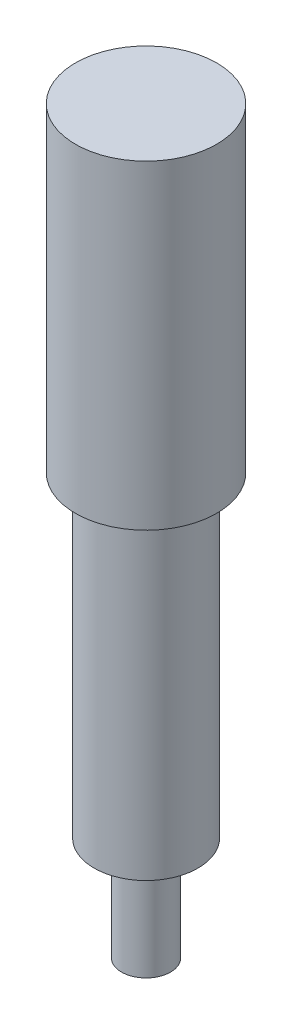
SolidWorks part; units mm, degrees
material "AISI 316 Annealed Stainless Steel Bar (SS)"
ref_plane "Front Plane" through (0, 0, 0) normal (0, 0, 1) x (1, 0, 0)
ref_plane "Top Plane" through (0, 0, 0) normal (0, 1, 0) x (1, 0, 0)
ref_plane "Right Plane" through (0, 0, 0) normal (1, 0, 0) x (0, 0, -1)
sketch "Sketch2" plane through (0, 0, 0) normal (0, 0, 1) x (1, 0, 0)
  line L0 (0, 0) -> (0, 508.8276) construction
  line L1 (0, 0) -> (6, 0)
  line L2 (0, 0) -> (0, 25.4)
  line L3 (0, 25.4) -> (6, 25.4)
  line L4 (6, 0) -> (6, 25.4)
  line L5 (0, 25.4) -> (12.721, 25.4)
  line L6 (0, 25.4) -> (0, 69.85)
  line L7 (0, 69.85) -> (12.721, 69.85)
  line L8 (12.721, 25.4) -> (12.721, 69.85)
  line L9 (0, 69.85) -> (12.721, 69.85)
  line L10 (0, 69.85) -> (0, 102.87)
  line L11 (0, 102.87) -> (12.721, 102.87)
  line L12 (12.721, 69.85) -> (12.721, 102.87)
  line L13 (0, 102.87) -> (17.272, 102.87)
  line L14 (0, 102.87) -> (0, 181.102)
  line L15 (0, 181.102) -> (17.272, 181.102)
  line L16 (17.272, 102.87) -> (17.272, 181.102)
  dimension "D1" = 78.232
  dimension "D2" = 17.272
  dimension "D4" = 33.02
  dimension "D3" = 12.721
  dimension "D5" = 44.45
  dimension "D6" = 12.721
  dimension "D7" = 25.4
  dimension "D8" = 6
revolve "Revolve1" add sketch "Sketch2" angle 360 about L0
equation "\"hole diamiter\"= 1.36in"
equation "\"wheel depth\"= 2.88"
equation "\"press_tolerance\"= 0.00165"
equation "\"wheel_connection\"= \"hole diamiter\"'https://at-machining.com/tolerance-press-fit/"
equation "\"D1@Sketch2\"=\"wheel depth\"+0.2"
equation "\"D2@Sketch2\"=\"wheel_connection\"/2"
equation "\"fitting depth\"= 1.3"
equation "\"D4@Sketch2\"=\"fitting depth\""
equation "\"bearing_id\"= 1"
equation "\"bearing_connection\"= \"bearing_id\" + \"press_tolerance\"'https://at-machining.com/tolerance-press-fit/"
equation "\"D3@Sketch2\"=\"bearing_connection\"/2"
equation "\"thread length\"= 1.75"
equation "\"major_diamiter\"= 0.9980'https://www.machiningdoctor.com/threadinfo/?tid=109"
equation "\"D5@Sketch2\"=\"thread length\""
equation "\"D6@Sketch2\"=\"bearing_connection\"/2"
equation "\"coupling diamiter\"= 12mm"
equation "\"coupling lenght\"=1"
equation "\"D7@Sketch2\"=\"coupling lenght\""
equation "\"D8@Sketch2\"=\"coupling diamiter\"/2"
